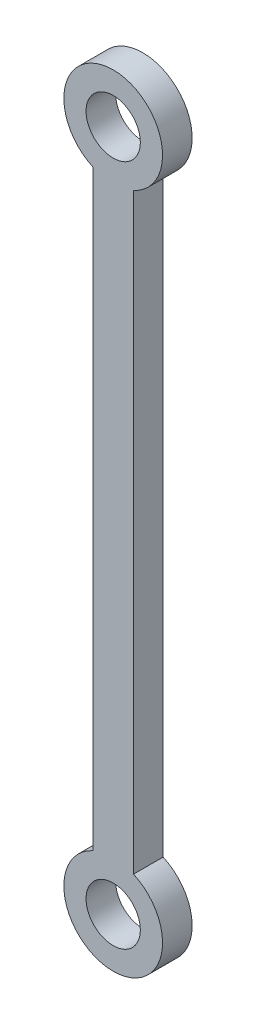
SolidWorks part; units mm, degrees
ref_plane "Front Plane" through (0, 0, 0) normal (0, 0, 1) x (1, 0, 0)
ref_plane "Top Plane" through (0, 0, 0) normal (0, 1, 0) x (1, 0, 0)
ref_plane "Right Plane" through (0, 0, 0) normal (1, 0, 0) x (0, 0, -1)
sketch "Sketch3" plane through (0, 0, 0) normal (0, 0, 1) x (1, 0, 0)
  line L3 (644.7499, -1231.5818) -> (644.7499, -1291.5818)
  line L5 (640.6253, -1231.5818) -> (640.6253, -1291.5818)
  arc A0 (644.7499, -1231.5818) -> (640.6253, -1231.5818) centre (642.6876, -1227.027) ccw
  arc A1 (640.6253, -1291.5818) -> (644.7499, -1291.5818) centre (642.6876, -1296.1367) ccw
  circle A2 centre (642.6876, -1296.1367) radius 2.75
  circle A3 centre (642.6876, -1227.027) radius 2.75
  point P3 (0, 0)
  point P8 (0, 0)
  dimension "D1" = 5.5
  dimension "D2" = 5
  dimension "D3" = 60
  dimension "D5" = 5
  dimension "D4" = 5.5
extrude "Boss-Extrude3" add sketch "Sketch3" along normal mid plane 3 separate body
